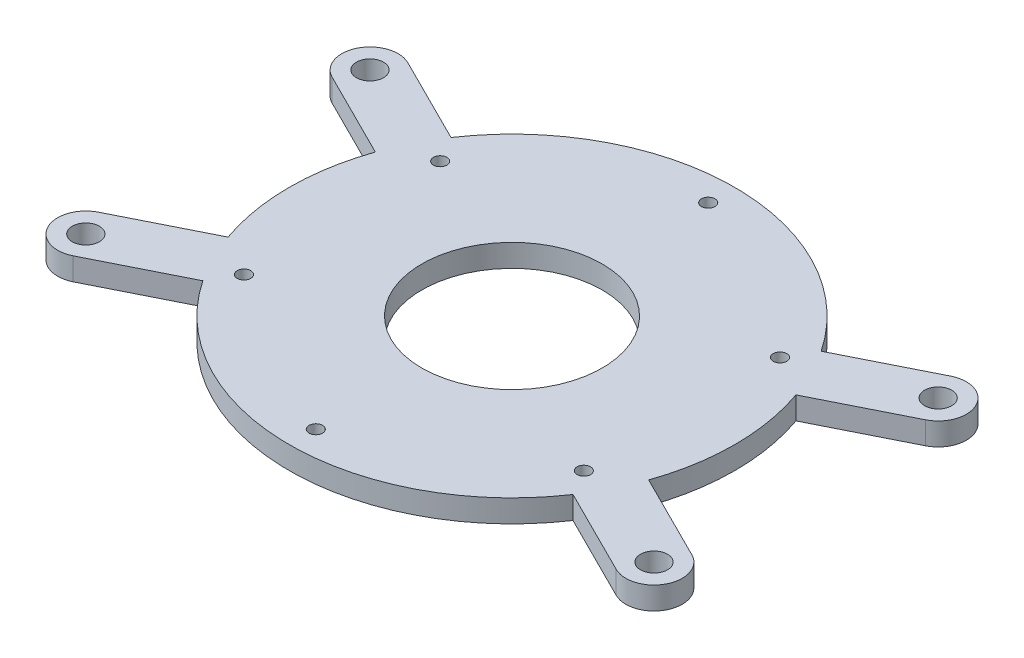
SolidWorks part; units mm, degrees
ref_plane "前视基准面" through (0, 0, 0) normal (0, 0, 1) x (1, 0, 0)
ref_plane "上视基准面" through (0, 0, 0) normal (0, 1, 0) x (1, 0, 0)
ref_plane "右视基准面" through (0, 0, 0) normal (1, 0, 0) x (0, 0, -1)
sketch "草图1" plane through (0, 0, 0) normal (0, 1, 0) x (1, 0, 0)
  line L0 (65.782, 25.9101) -> (46.6233, 16.3287)
  line L1 (60.1908, 37.0899) -> (41.0322, 27.5085)
  line L2 (0, 135.0816) -> (0, -134.5462) construction
  line L3 (161.8892, 80.9621) -> (-87.1466, -43.5827) construction
  line L7 (-65.782, 25.9101) -> (-46.6233, 16.3287)
  line L8 (-50, 21.5) -> (50, 21.5) construction
  line L9 (-50, 21.5) -> (-50, -21.5) construction
  line L10 (-50, -21.5) -> (50, -21.5) construction
  line L11 (50, 21.5) -> (50, -21.5) construction
  line L12 (-60.1908, 37.0899) -> (-41.0322, 27.5085)
  line L13 (-133.256, 0) -> (145.6129, 0) construction
  line L14 (65.782, -25.9101) -> (46.6233, -16.3287)
  line L15 (60.1908, -37.0899) -> (41.0322, -27.5085)
  line L16 (-65.782, -25.9101) -> (-46.6233, -16.3287)
  line L17 (-60.1908, -37.0899) -> (-41.0322, -27.5085)
  circle A0 centre (0, 0) radius 20
  circle A1 centre (0, 0) radius 49.4
  circle A2 centre (62.9864, 31.5) radius 6.25
  circle A6 centre (-62.9864, 31.5) radius 6.25
  circle A7 centre (62.9864, -31.5) radius 6.25
  circle A8 centre (-62.9864, -31.5) radius 6.25
  point P19 (0, 21.5)
  point P20 (50, 0)
  point P41 (0, 0)
  dimension "D2" = 12.5
  dimension "D5" = 98.8
  dimension "D7" = 40
  dimension "D1" = 63.43
  dimension "D3" = 100
  dimension "D4" = 43
  dimension "D6" = 10
extrude "凸台-拉伸1" add sketch "草图1" along normal blind 5 contours A1 A0 | L12 A6 L7 A1 | A8 L17 A1 L16 | A8 | L15 A7 L14 A1 | A7 | A2 | A2 L1 A1 L0
sketch "草图2" plane through (0, 5, 0) normal (0, 1, 0) x (1, 0, 0)
  line L0 (0, 78.1952) -> (0, -57.2274) construction
  line L1 (-93.9988, 0) -> (82.0699, 0) construction
  circle A0 centre (-62.9864, 31.5) radius 3
  arc A1 (-60.1908, 37.0899) -> (-65.782, 25.9101) centre (-62.9864, 31.5) ccw construction
  dimension "D1" = 6
extrude "切除-拉伸1" cut sketch "草图2" against normal up to next
mirror "镜向1" about plane through (0, 0, 0) normal (0, 0, 1) of "切除-拉伸1"
mirror "镜向2" about plane through (0, 0, 0) normal (1, 0, 0) of "镜向1", "切除-拉伸1"
sketch "草图3" plane through (0, 0, 0) normal (0, -1, 0) x (1, 0, 0)
  circle A0 centre (0, 43.5) radius 1.5
  dimension "D1" = 3
  dimension "D2" = 43.5
extrude "切除-拉伸2" cut sketch "草图3" against normal through all
cosmetic thread "装饰螺纹线1" parameters "D2"=4
pattern_circular "阵列(圆周)1" count 6 over 360 about axis through (0, 0, 0) along (0, 1, 0) of "切除-拉伸2"
cosmetic thread "装饰螺纹线2" parameters "D2"=4
cosmetic thread "装饰螺纹线3" parameters "D2"=4
cosmetic thread "装饰螺纹线4" parameters "D2"=4
cosmetic thread "装饰螺纹线5" parameters "D2"=4
cosmetic thread "装饰螺纹线6" parameters "D2"=4
